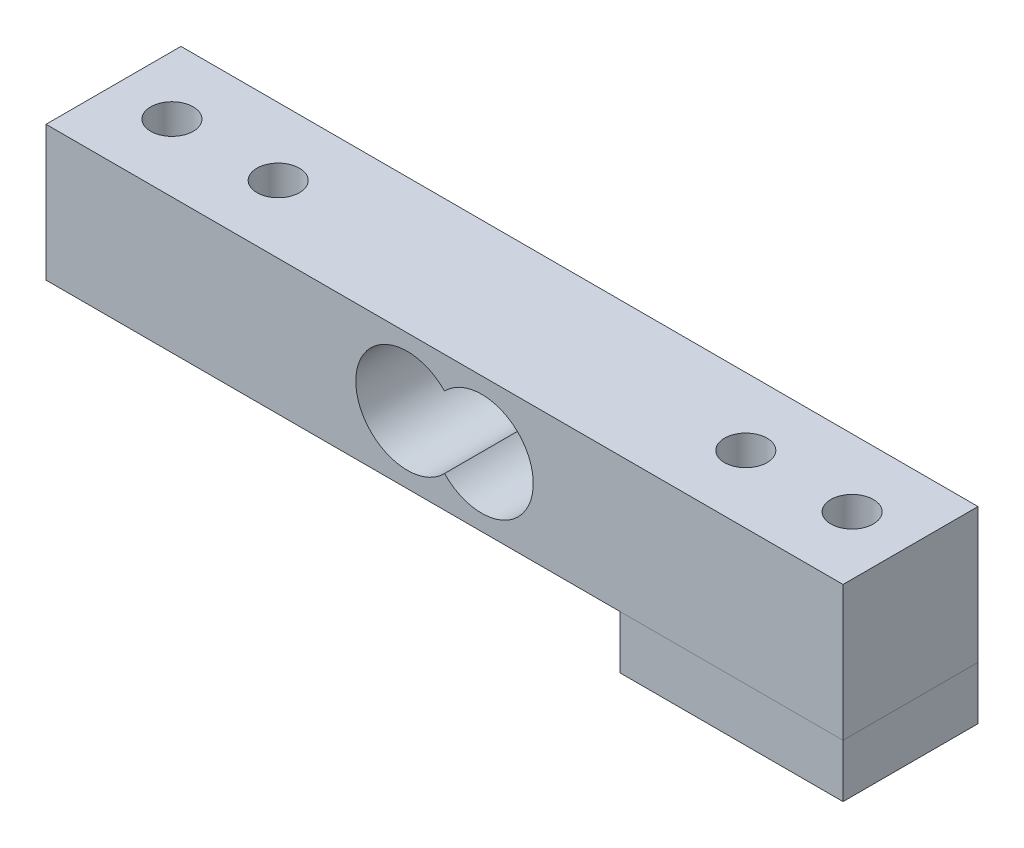
SolidWorks part; units mm, degrees
ref_plane "Front Plane" through (0, 0, 0) normal (0, 0, 1) x (1, 0, 0)
ref_plane "Top Plane" through (0, 0, 0) normal (0, 1, 0) x (1, 0, 0)
ref_plane "Right Plane" through (0, 0, 0) normal (1, 0, 0) x (0, 0, -1)
sketch "Sketch1" plane through (0, 0, 0) normal (0, 1, 0) x (1, 0, 0)
  line L0 (-27, 6.35) -> (-27, -6.35) construction
  line L1 (-37.5, -6.35) -> (37.5, -6.35)
  line L2 (-37.5, -6.35) -> (-37.5, 6.35)
  line L3 (-37.5, 6.35) -> (37.5, 6.35)
  line L4 (37.5, -6.35) -> (37.5, 6.35)
  line L5 (-37.5, -6.35) -> (37.5, 6.35) construction
  line L6 (-37.5, 6.35) -> (37.5, -6.35) construction
  circle A0 centre (-32, 0) radius 2
  circle A1 centre (-22, 0) radius 2
  circle A2 centre (22, 0) radius 2
  circle A3 centre (32, 0) radius 2
  point P0 (0, 0)
  dimension "D7" = 4
  dimension "D1" = 75
  dimension "D2" = 12.7
  dimension "D3" = 10
  dimension "D4" = 10
  dimension "D5" = 44
  dimension "D6" = 22
  dimension "D8" = 5
extrude "Boss-Extrude1" add sketch "Sketch1" along normal blind 12.7
sketch "Sketch2" plane through (0, 0, 6.35) normal (0, 0, 1) x (1, 0, 0)
  line L0 (-37.5, 12.7) -> (37.5, 0) construction
  line L1 (37.5, 12.7) -> (37.5, 0) construction
  line L2 (-37.5, 0) -> (37.5, 0) construction
  line L3 (37.5, 12.7) -> (-37.5, 0) construction
  line L4 (-37.5, 12.7) -> (37.5, 12.7) construction
  circle A0 centre (-3.5, 6.35) radius 4.85
  circle A1 centre (3.5, 6.35) radius 4.85
  point P18 (0, 6.35)
  dimension "D3" = 9.7
  dimension "D1" = 7
  dimension "D2" = 3.5
extrude "Cut-Extrude1" cut sketch "Sketch2" against normal up to surface (12.7 mm away) contours A1 A0 | A0 A1 | A0 A1 up to face at (0, 6.35, -6.35)
sketch "Sketch3" plane through (0, 0, 0) normal (0, -1, 0) x (1, 0, 0)
  line L0 (-37.5, 6.35) -> (37.5, 6.35) construction
  line L1 (37.5, -6.35) -> (16.5, -6.35)
  line L2 (37.5, -6.35) -> (37.5, 6.35)
  line L3 (37.5, 6.35) -> (16.5, 6.35)
  line L4 (16.5, -6.35) -> (16.5, 6.35)
  circle A0 centre (32, 0) radius 2 construction
  circle A1 centre (22, 0) radius 2 construction
  circle A2 centre (32, 0) radius 2 construction
  circle A3 centre (22, 0) radius 2 construction
  circle A4 centre (32, 0) radius 2.25
  circle A5 centre (22, 0) radius 2.25
  dimension "D2" = 37.5
  dimension "D1" = 5.5
  dimension "D3" = 5.5
  dimension "D4" = 0.25
extrude "Boss-Extrude2" add sketch "Sketch3" along normal blind 5 separate body
ref_plane "Plane1" through (0, 0, 0) normal (0, 0, -1) x (-1, 0, 0)
ref_plane "Plane3" through (-27, 0, 0) normal (-1, 0, 0) x (0, 0, 1)
equation "\"D6@Sketch1\"=\"D5@Sketch1\"/2"
equation "\"D2@Sketch2\"=\"D1@Sketch2\"/2"
equation "\"D3@Sketch3\"=\"D1@Sketch3\""
equation "\"D8@Sketch1\"=\"D3@Sketch1\"/2"
